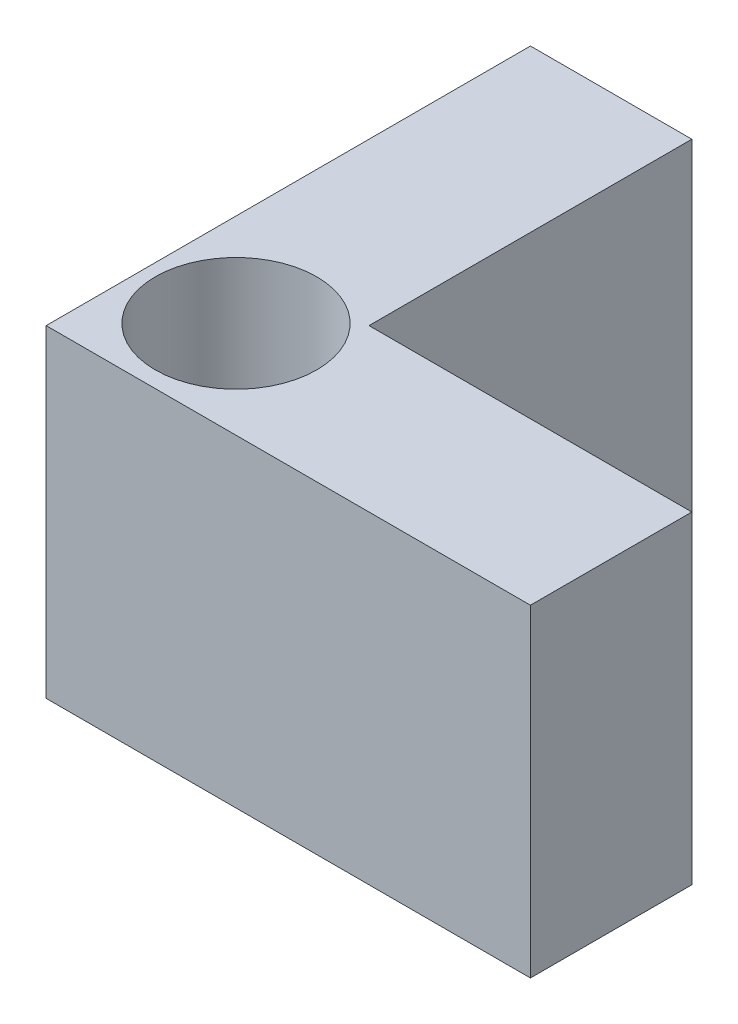
SolidWorks part; units mm, degrees
ref_plane "Front Plane" through (0, 0, 0) normal (0, 0, 1) x (1, 0, 0)
ref_plane "Top Plane" through (0, 0, 0) normal (0, 1, 0) x (1, 0, 0)
ref_plane "Right Plane" through (0, 0, 0) normal (1, 0, 0) x (0, 0, -1)
sketch "Sketch1" plane through (0, 0, 0) normal (0, 1, 0) x (1, 0, 0)
  line L0 (0, 15) -> (0, 0)
  line L3 (0, 15) -> (5, 15)
  line L4 (5, 5) -> (5, 15)
  line L7 (5, 5) -> (15, 5)
  line L8 (15, 0) -> (15, 5)
  line L9 (0, 0) -> (15, 0)
  circle A0 centre (2.8799, 3.0008) radius 2.5
  dimension "D4" = 5
  dimension "D1" = 15
  dimension "D2" = 15
  dimension "D3" = 5
extrude "Boss-Extrude1" add sketch "Sketch1" along normal blind 10
